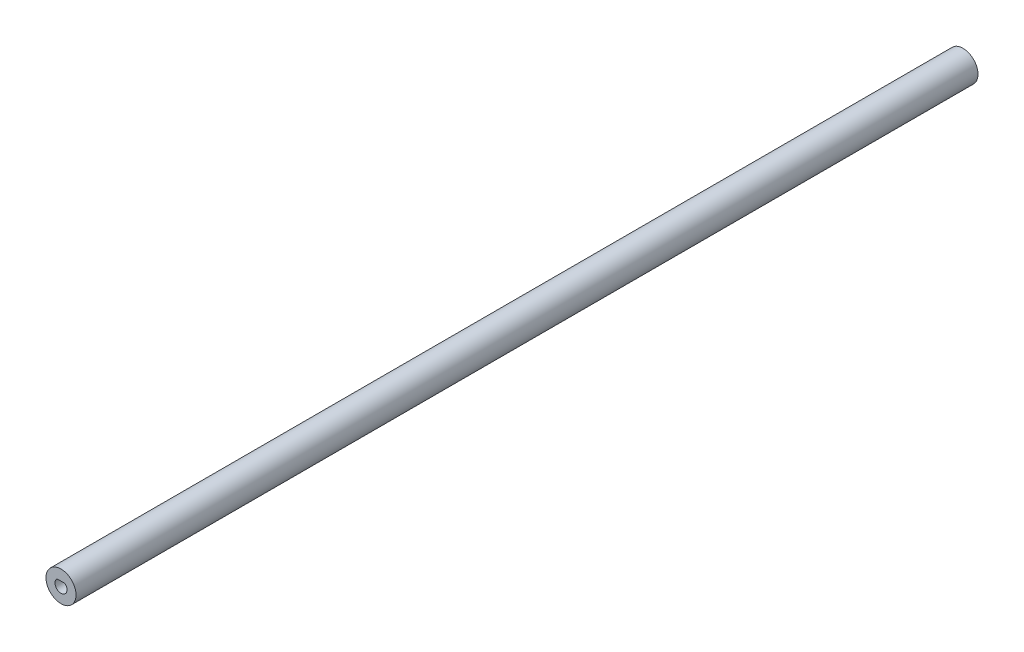
SolidWorks part; units mm, degrees
ref_plane "Front Plane" through (0, 0, 0) normal (0, 0, 1) x (1, 0, 0)
ref_plane "Top Plane" through (0, 0, 0) normal (0, 1, 0) x (1, 0, 0)
ref_plane "Right Plane" through (0, 0, 0) normal (1, 0, 0) x (0, 0, -1)
sketch "Sketch1" plane through (0, 0, 0) normal (0, 0, 1) x (1, 0, 0)
  circle A0 centre (-21.9281, 1.412) radius 5
  dimension "D1" = 10
extrude "Boss-Extrude1" add sketch "Sketch1" along normal blind 300
sketch "Sketch3" plane through (0, 0, 300) normal (0, 0, 1) x (1, 0, 0)
  line L0 (-21.9281, 6.412) -> (-21.9281, -3.588) construction
  line L1 (-26.9281, 1.412) -> (-16.9281, 1.412) construction
  line L3 (-23.251, 2.912) -> (-20.6053, 2.912)
  circle A0 centre (-21.9281, 1.412) radius 5 construction
  arc A1 (-23.251, 2.912) -> (-20.6053, 2.912) centre (-21.9281, 1.412) ccw
  point P8 (0, 0)
  point P9 (-21.9281, 2.912)
  point P10 (0, 0)
  dimension "D1" = 4
  dimension "D2" = 1.5
extrude "Cut-Extrude2" cut sketch "Sketch3" against normal blind 8
